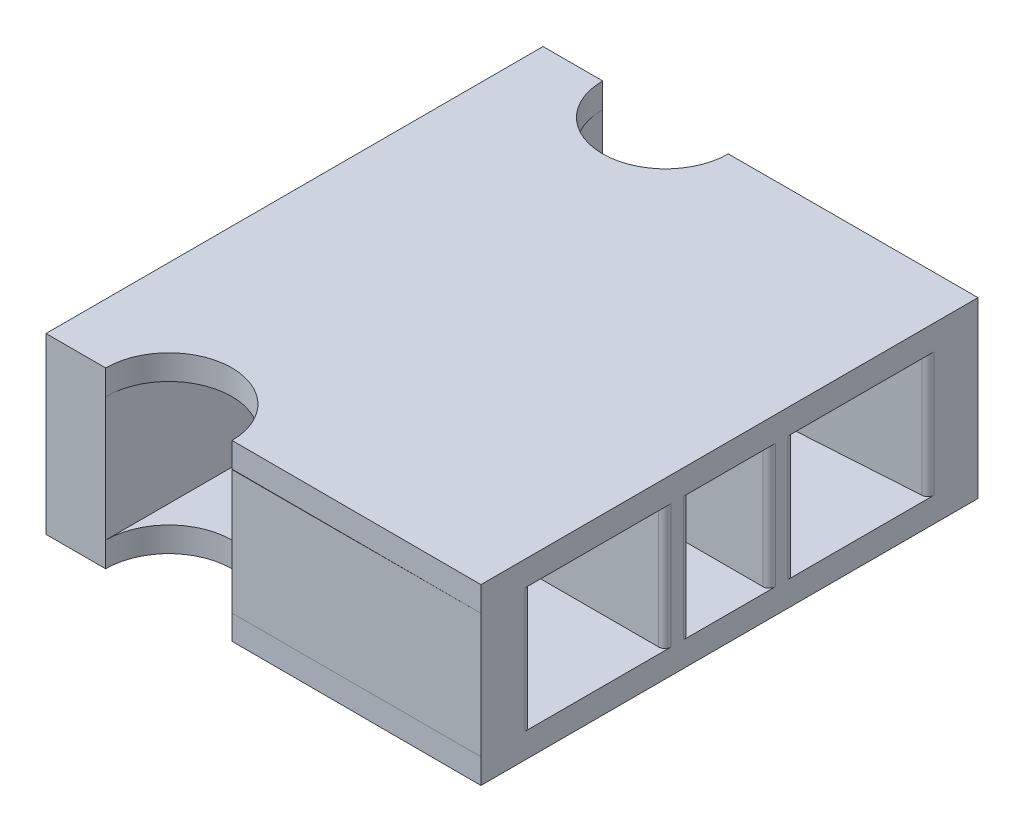
SolidWorks part; units mm, degrees
ref_plane "Alzado" through (0, 0, 0) normal (0, 0, 1) x (1, 0, 0)
ref_plane "Planta" through (0, 0, 0) normal (0, 1, 0) x (1, 0, 0)
ref_plane "Vista lateral" through (0, 0, 0) normal (1, 0, 0) x (0, 0, -1)
sketch "Croquis1" plane through (0, 0, 0) normal (0, 1, 0) x (1, 0, 0)
  line L0 (-17.5304, 19.9991) -> (17.5304, 19.9991) construction
  line L1 (17.5304, 19.9991) -> (-2.4991, 19.9991)
  line L2 (-17.5304, 19.9991) -> (-17.5304, -20.0009) construction
  line L3 (-17.5304, -20.0009) -> (17.5304, -20.0009) construction
  line L4 (17.5304, -20.0009) -> (17.5304, -15.9974) construction
  line L5 (-2.4991, 19.9991) -> (-2.5304, 19.9681)
  line L6 (-2.5304, 19.9681) -> (-2.5304, 14.7182)
  line L7 (-2.5304, 14.7182) -> (17.5304, 16.0003)
  line L8 (17.5304, 16.0003) -> (17.5304, 19.9991)
  line L9 (17.5304, -20.0009) -> (-2.4991, -20.0009)
  line L10 (-2.4991, -20.0009) -> (-2.5305, -19.9696)
  line L11 (-2.5305, -19.9696) -> (-2.5305, -14.7108)
  line L12 (-2.5305, -14.7108) -> (17.5304, -15.9974)
  line L13 (17.5304, -15.9974) -> (17.5304, -20.0009)
  line L14 (-12.6701, 19.9991) -> (-17.5304, 19.9991)
  line L15 (-17.5304, 19.9991) -> (-17.5304, -20.0009)
  line L16 (-17.5304, -20.0009) -> (-12.6701, -20.0009)
  line L17 (-12.6701, 19.9991) -> (-12.6701, -20.0009)
  line L20 (17.5304, 16.0003) -> (17.5304, 19.9991) construction
  line L21 (17.5293, 16.0182) -> (17.5293, -16.0152) construction
extrude "Saliente-Extruir1" add sketch "Croquis1" along normal mid plane 10
sketch "Croquis3" plane through (0, 5, 0) normal (0, 1, 0) x (1, 0, 0)
  line L0 (-17.5304, 19.9991) -> (-12.6701, 19.9991)
  line L1 (-17.5304, 19.9991) -> (-17.5304, -20.0009)
  line L2 (-17.5304, -20.0009) -> (-12.6701, -20.0009)
  line L3 (-2.5305, -19.9696) -> (17.5304, -20.0009)
  line L4 (17.5304, -20.0009) -> (17.5304, 19.9991)
  line L5 (17.5304, 19.9991) -> (-2.5304, 19.9681)
  arc A2 (-12.6701, 19.9991) -> (-2.5304, 19.9681) centre (-7.6002, 19.9836) ccw
  arc A3 (-12.6701, -20.0009) -> (-2.5305, -19.9696) centre (-7.6003, -19.9852) cw
extrude "Saliente-Extruir2" add sketch "Croquis3" along normal blind 2
mirror "Simetría1" about plane through (0, 0, 0) normal (0, 1, 0) of "Saliente-Extruir2"
fillet "Redondeo1" radius 0.5 1 edges at (-2.5305, 0, 14.7108)
fillet "Redondeo2" radius 0.5 1 edges at (-2.5304, 0, -14.7182)
fillet "Redondeo3" radius 0.5 2 edges at (17.5304, 0, -16.0003) (17.5304, 0, 15.9974)
sketch "Croquis5" plane through (0, 0, 0) normal (0, 1, 0) x (1, 0, 0)
  line L0 (17.5304, -5.1985) -> (17.5304, -3.1985)
  line L1 (17.5304, -16.4663) -> (17.5304, 16.4693) construction
  line L2 (17.5304, 3.2015) -> (-12.6701, 3.2015)
  line L3 (-12.6701, -19.9696) -> (-12.6701, 19.9681) construction
  line L4 (-12.6701, 3.2015) -> (-12.6701, 5.2015)
  line L5 (-12.6701, 5.2015) -> (17.5304, 5.2015)
  line L6 (17.5304, 5.2015) -> (17.5304, 3.2015)
  line L7 (18.3108, 0.0015) -> (-25.4962, 0.0015) construction
  line L8 (-12.6701, -5.1985) -> (17.5304, -5.1985)
  line L9 (-12.6701, -3.1985) -> (-12.6701, -5.1985)
  line L10 (17.5304, -3.1985) -> (-12.6701, -3.1985)
  point P5 (17.5304, 0.0015)
  dimension "D1" = 6.4
  dimension "D2" = 2
extrude "Saliente-Extruir3" add sketch "Croquis5" along normal mid plane 10
fillet "Redondeo4" radius 0.5 4 edges at (17.5304, 0, -5.2015) (17.5304, 0, -3.2015) (17.5304, 0, 3.1985) (17.5304, 0, 5.1985)
sketch "Croquis6" plane through (0, 7, 0) normal (0, 1, 0) x (1, 0, 0)
  line L6 (-17.5304, 19.9991) -> (-17.4704, 19.9991)
  line L7 (-17.5304, 19.9991) -> (-17.5304, -20.0009)
  line L8 (-17.5304, -20.0009) -> (-17.4704, -20.0009)
  line L9 (-17.4704, 19.9991) -> (-17.4704, -20.0009)
  dimension "D1" = 40
  dimension "D2" = 0.06
extrude "Cortar-Extruir4" cut sketch "Croquis6" against normal blind 17
